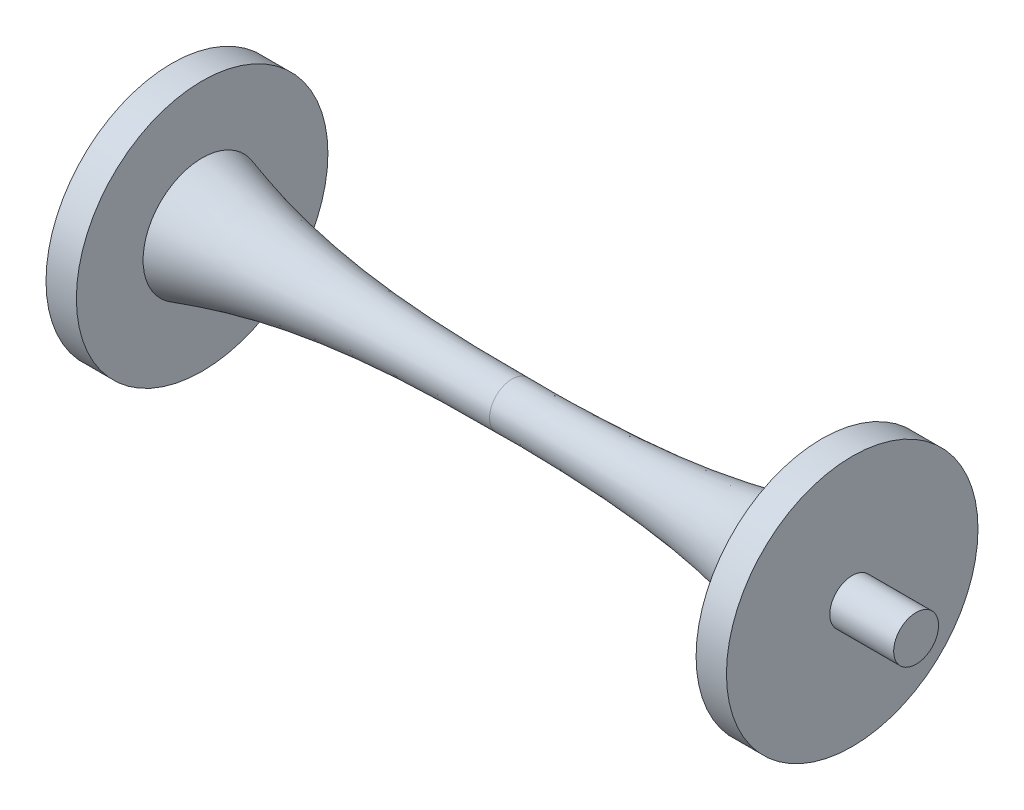
SolidWorks part; units mm, degrees
ref_plane "Front Plane" through (0, 0, 0) normal (0, 0, 1) x (1, 0, 0)
ref_plane "Top Plane" through (0, 0, 0) normal (0, 1, 0) x (1, 0, 0)
ref_plane "Right Plane" through (0, 0, 0) normal (1, 0, 0) x (0, 0, -1)
sketch "Sketch1" plane through (0, 0, 0) normal (0, 1, 0) x (1, 0, 0)
  line L0 (-50, 10.1523) -> (-50, 3.2995)
  line L1 (-50, 3.2995) -> (-59.3909, 3.2995)
  line L2 (-59.3909, 3.2995) -> (-59.3909, 0)
  line L3 (0, 0) -> (-155.0761, 0) construction
  line L4 (0, 0) -> (0, 54.8223) construction
  line L5 (-59.3909, 0) -> (59.3909, 0)
  line L6 (59.3909, 0) -> (59.3909, 3.2995)
  line L7 (-50, 10.1523) -> (-50, 18.4844)
  line L8 (-50, 18.4844) -> (-45.5383, 18.4844)
  line L9 (-45.5383, 18.4844) -> (-45.5383, 8.678)
  line L10 (50, 3.2995) -> (59.3909, 3.2995)
  line L11 (50, 10.1523) -> (50, 3.2995)
  line L12 (50, 10.1523) -> (50, 18.4844)
  line L13 (45.5383, 18.4844) -> (45.5383, 8.678)
  line L14 (50, 18.4844) -> (45.5383, 18.4844)
  spline S0 degree 3 poles (0, 3.2995) (-14.1343, 3.2478) (-28.3527, 3.9644) (-42.9361, 7.8762) (-45.5383, 8.678) knots 0 0 0 0 0.749456 0.909413 0.909413 0.909413 0.909413
  spline S3 degree 3 poles (0, 3.2995) (14.1343, 3.2478) (28.3527, 3.9644) (42.9361, 7.8762) (45.5383, 8.678) knots 0 0 0 0 0.749456 0.909413 0.909413 0.909413 0.909413
  point P11 (-59.3909, 0)
  point P23 (59.3909, 0)
  dimension "D1" = 100
revolve "Revolve1" add sketch "Sketch1" angle 360 about L3
